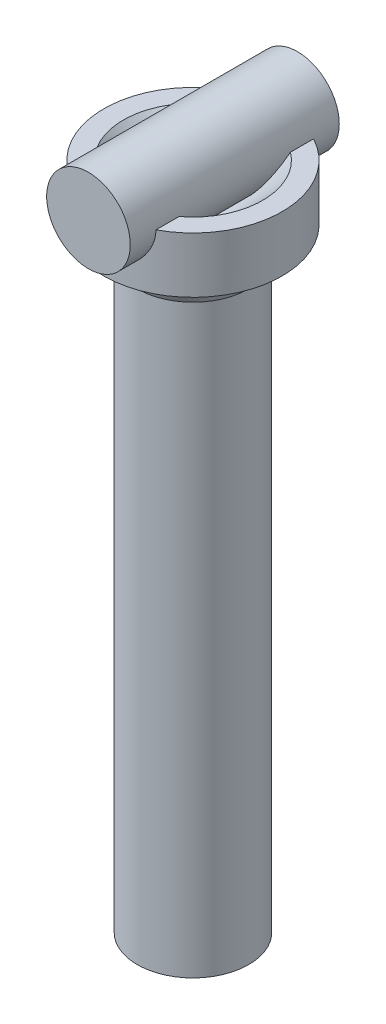
SolidWorks part; units mm, degrees
ref_plane "Front Plane" through (0, 0, 0) normal (0, 0, 1) x (1, 0, 0)
ref_plane "Top Plane" through (0, 0, 0) normal (0, 1, 0) x (1, 0, 0)
ref_plane "Right Plane" through (0, 0, 0) normal (1, 0, 0) x (0, 0, -1)
sketch "Sketch1" plane through (0, 0, 0) normal (0, 0, 1) x (1, 0, 0)
  line L0 (0, 0) -> (0, 22)
  line L1 (0, 22) -> (0.5, 22)
  line L2 (0.5, 22) -> (2.5, 24)
  line L3 (2.5, 24) -> (3.2, 24)
  line L4 (3.2, 24) -> (3.2, 22)
  line L5 (3.2, 22) -> (2.4095, 22)
  line L6 (2.4095, 22) -> (2, 21)
  line L7 (2, 21) -> (2, 0)
  line L8 (2, 0) -> (0, 0)
  dimension "D1" = 2
  dimension "D2" = 22
  dimension "D3" = 0.5
  dimension "D4" = 135
  dimension "D5" = 2
  dimension "D6" = 3.2
  dimension "D7" = 2
  dimension "D8" = 1
revolve "Revolve1" add sketch "Sketch1" angle 360 about L0
sketch "Sketch2" plane through (0, 0, 0) normal (0, 0, 1) x (1, 0, 0)
  line L0 (3.2, 24) -> (-3.2, 24) construction
  circle A0 centre (0, 24) radius 1.5
  dimension "D1" = 3
extrude "Boss-Extrude1" add sketch "Sketch2" along normal mid plane 7.5
